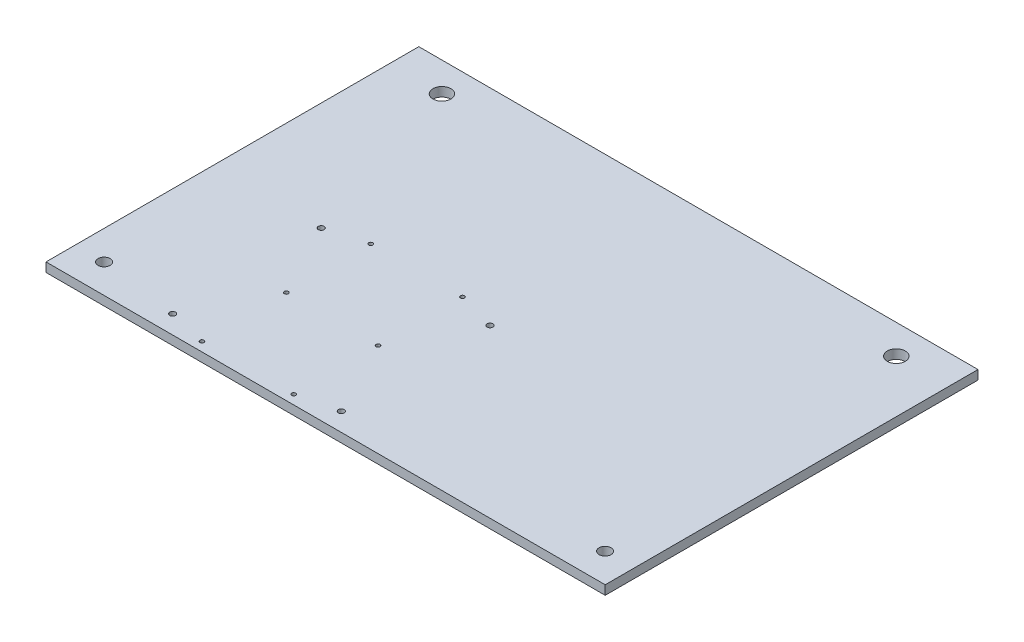
SolidWorks part; units mm, degrees
ref_plane "Front Plane" through (0, 0, 0) normal (0, 0, 1) x (1, 0, 0)
ref_plane "Top Plane" through (0, 0, 0) normal (0, 1, 0) x (1, 0, 0)
ref_plane "Right Plane" through (0, 0, 0) normal (1, 0, 0) x (0, 0, -1)
sketch "Sketch1" plane through (0, 0, 0) normal (0, 1, 0) x (1, 0, 0)
  line L1 (0, 0) -> (304.8, 0)
  line L2 (0, 0) -> (0, -203.2)
  line L3 (0, -203.2) -> (304.8, -203.2)
  line L4 (304.8, 0) -> (304.8, -203.2)
  dimension "D1" = 203.2
  dimension "D2" = 304.8
extrude "Boss-Extrude1" add sketch "Sketch1" along normal blind 5
sketch "Sketch2" plane through (0, 5, 0) normal (0, 1, 0) x (1, 0, 0)
  line L0 (152.4, 0) -> (152.4, -203.2) construction
  line L1 (304.8, 0) -> (0, 0) construction
  line L2 (0, -203.2) -> (304.8, -203.2) construction
  line L3 (0, -101.6) -> (304.8, -101.6) construction
  line L4 (0, 0) -> (0, -203.2) construction
  line L5 (304.8, -203.2) -> (304.8, 0) construction
  circle A2 centre (288.925, -187.4139) radius 3.2639
  circle A3 centre (15.875, -187.4139) radius 3.2639
  circle A4 centre (28.575, -15.9639) radius 3.2639
  circle A5 centre (276.225, -15.9639) radius 3.2639
  dimension "D1" = 85.8139
  dimension "D4" = 6.5278
  dimension "D7" = 171.45
  dimension "D3" = 247.65
  dimension "D2" = 12.7
  dimension "D5" = 85.8139
  dimension "D6" = 273.05
sketch "locations for led holes" plane through (0, 5, 0) normal (0, 1, 0) x (1, 0, 0)
  line L1 (0, -203.2) -> (304.8, -203.2) construction
  line L2 (0, 0) -> (0, -203.2) construction
  point P0 (80, -198.2)
  point P1 (80, -152.2)
  point P2 (80, -106.2)
  point P3 (130, -106.2)
  point P4 (130, -152.2)
  point P5 (130, -198.2)
  point P6 (0, 0)
  dimension "D1" = 46
  dimension "D2" = 46
  dimension "D3" = 50
  dimension "D4" = 5
  dimension "D5" = 80
hole_wizard "clearance holes for led panel" positions "Sketch4" profile "Sketch5" hole size "M2" standard "ISO" end condition through all
sketch "Sketch4" plane through (0, 5, 0) normal (0, 1, 0) x (1, 0, 0)
  point P0 (80, -106.2)
  point P3 (130, -106.2)
  point P6 (130, -152.2)
  point P9 (80, -152.2)
  point P12 (80, -198.2)
  point P15 (130, -198.2)
sketch "Sketch5" plane through (80, 5, 106.2) normal (1, 0, 0) x (0, 0, 1)
  line L0 (0, 0) -> (0, 5)
  line L1 (0, 5) -> (1.1, 5)
  line L2 (1.1, 5) -> (1.1, 0)
  line L5 (1.1, 0) -> (0, 0)
  line L11 (0, -6.35) -> (0, 107.95) construction
  dimension "Thru Hole Dia." = 2.2
  dimension "Thru Hole Depth" = 5
sketch "location of holes for solar mount" plane through (0, 5, 0) normal (0, 1, 0) x (1, 0, 0)
  line L0 (0, -203.2) -> (304.8, -203.2) construction
  line L2 (0, 0) -> (0, -203.2) construction
  point P0 (59, -193.2)
  point P1 (151, -193.2)
  point P2 (151, -112.2)
  point P3 (59, -112.2)
  point P4 (0, 0)
  dimension "D1" = 92
  dimension "D2" = 81
  dimension "D3" = 10
  dimension "D4" = 59
hole_wizard "M3 Clearance Hole1" positions "Sketch7" profile "Sketch8" hole size "M3" standard "ISO" end condition through all
sketch "Sketch7" plane through (0, 5, 0) normal (0, 1, 0) x (1, 0, 0)
  point P0 (59, -112.2)
  point P3 (151, -112.2)
  point P6 (151, -193.2)
  point P9 (59, -193.2)
sketch "Sketch8" plane through (59, 5, 112.2) normal (1, 0, 0) x (0, 0, 1)
  line L0 (0, 0) -> (0, 5)
  line L1 (0, 5) -> (1.6, 5)
  line L2 (1.6, 5) -> (1.6, 0)
  line L5 (1.6, 0) -> (0, 0)
  line L11 (0, -6.35) -> (0, 107.95) construction
  dimension "Thru Hole Dia." = 3.2
  dimension "Thru Hole Depth" = 5
hole_wizard "1/4 Clearance Hole1" positions "Sketch9" profile "Sketch10" hole size "1/4" standard "ANSI Inch" end condition through all
sketch "Sketch9" plane through (0, 5, 0) normal (0, 1, 0) x (1, 0, 0)
  point P0 (15.875, -187.4139)
  point P3 (288.925, -187.4139)
sketch "Sketch10" plane through (15.875, 5, 187.4139) normal (1, 0, 0) x (0, 0, 1)
  line L0 (0, 0) -> (0, 5)
  line L1 (0, 5) -> (3.2639, 5)
  line L2 (3.2639, 5) -> (3.2639, 0)
  line L5 (3.2639, 0) -> (0, 0)
  line L11 (0, -6.35) -> (0, 107.95) construction
  dimension "Thru Hole Dia." = 6.5278
  dimension "Thru Hole Depth" = 5
hole_wizard "3/8 Clearance Hole1" positions "Sketch15" profile "Sketch16" hole size "3/8" standard "ANSI Inch" end condition through all
sketch "Sketch15" plane through (0, 5, 0) normal (0, 1, 0) x (1, 0, 0)
  point P0 (28.575, -15.9639)
  point P3 (276.225, -15.9639)
sketch "Sketch16" plane through (28.575, 5, 15.9639) normal (1, 0, 0) x (0, 0, 1)
  line L0 (0, 0) -> (0, 5)
  line L1 (0, 5) -> (4.9022, 5)
  line L2 (4.9022, 5) -> (4.9022, 0)
  line L5 (4.9022, 0) -> (0, 0)
  line L11 (0, -6.35) -> (0, 107.95) construction
  dimension "Thru Hole Dia." = 9.8044
  dimension "Thru Hole Depth" = 5
